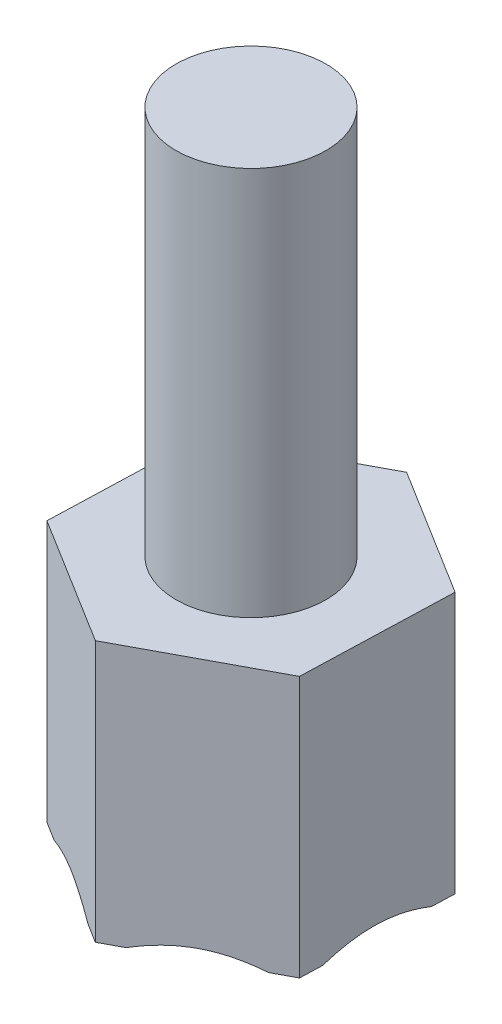
SolidWorks part; units mm, degrees
ref_plane "前视基准面" through (0, 0, 0) normal (0, 0, 1) x (1, 0, 0)
ref_plane "上视基准面" through (0, 0, 0) normal (0, 1, 0) x (1, 0, 0)
ref_plane "右视基准面" through (0, 0, 0) normal (1, 0, 0) x (0, 0, -1)
sketch "草图1" plane through (0, 0, 0) normal (0, 1, 0) x (1, 0, 0)
  line L1 (2.3046, -1.4325) -> (2.3929, 1.2796)
  line L2 (2.3929, 1.2796) -> (0.0883, 2.7121)
  line L3 (0.0883, 2.7121) -> (-2.3046, 1.4325)
  line L4 (-2.3046, 1.4325) -> (-2.3929, -1.2796)
  line L5 (-2.3929, -1.2796) -> (-0.0883, -2.7121)
  line L6 (-0.0883, -2.7121) -> (2.3046, -1.4325)
  circle A0 centre (0, 0) radius 2.35 construction
  dimension "D1" = 4.7
extrude "凸台-拉伸1" add sketch "草图1" along normal blind 4.7
hole_wizard "#10-24 螺纹孔1" positions "草图3" profile "草图2" tap size "#10-24" standard "Ansi Inch"
sketch "草图3" plane through (0, 0, 0) normal (0, -1, 0) x (1, 0, 0)
  point P1 (0, 0)
sketch "草图2" plane through (0, 0, 0) normal (1, 0, 0) x (0, 0, -1)
  line L0 (0, 0) -> (0, 4)
  line L1 (0, 4) -> (1.8986, 4)
  line L2 (1.8986, 4) -> (1.8986, 0.635)
  line L3 (1.8986, 0.635) -> (2.5337, 0)
  line L5 (2.5337, 0) -> (0, 0)
  line L6 (-1.8986, 0.635) -> (-2.5337, 0) construction
  line L10 (0, 4) -> (-1.8986, 4) construction
  line L11 (0, -6.35) -> (0, 107.95) construction
  dimension "螺纹孔钻头直径" = 3.7973
  dimension "螺纹孔钻头深度" = 4
  dimension "近端锥形沉头孔直径" = 5.0673
  dimension "近端锥形沉头孔角度" = 90
  dimension "导头角度" = 180
cosmetic thread "孔螺蚊线3" parameters "D1"=4, "D2"=4.826
sketch "草图5" plane through (0, 4.7, 0) normal (0, 1, 0) x (-1, 0, 0)
  circle A0 centre (0, 0) radius 1.35
  dimension "D1" = 2.7
extrude "凸台-拉伸2" add sketch "草图5" along direction (0, -1, 0) on the side of the normal offset from surface (7 mm away) 11.7
